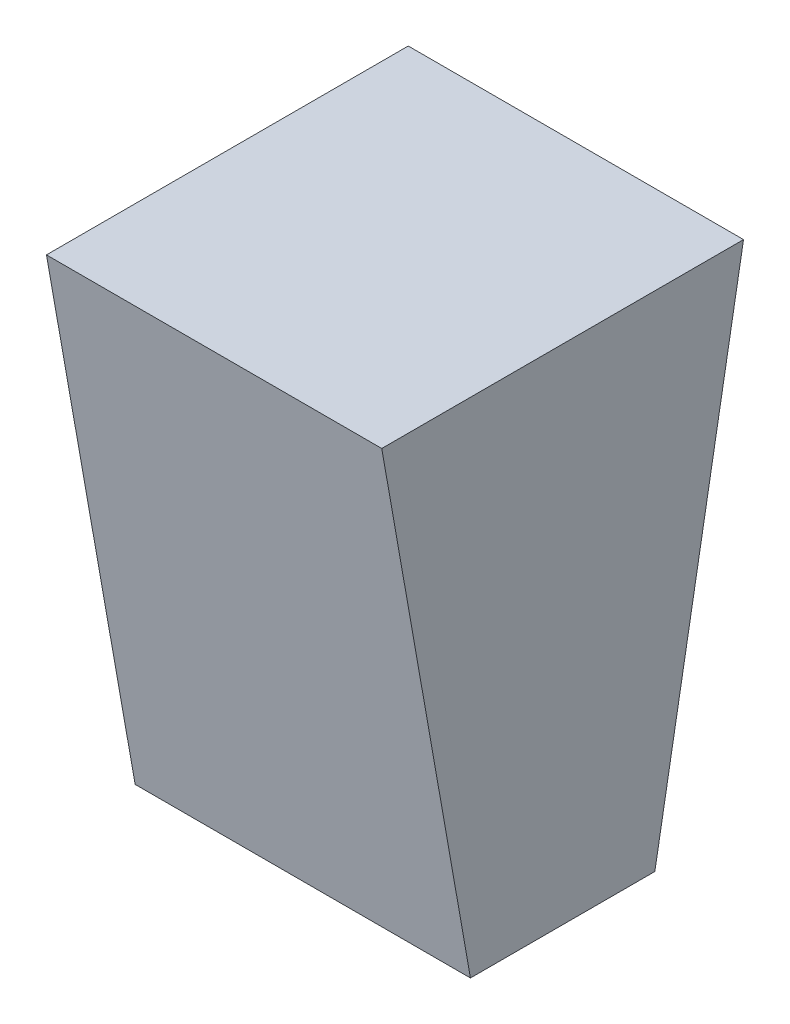
SolidWorks part; units mm, degrees
ref_plane "Alzado" through (0, 0, 0) normal (0, 0, 1) x (1, 0, 0)
ref_plane "Planta" through (0, 0, 0) normal (0, 1, 0) x (1, 0, 0)
ref_plane "Vista lateral" through (0, 0, 0) normal (1, 0, 0) x (0, 0, -1)
sketch "Croquis1" plane through (0, 0, 0) normal (1, 0, 0) x (0, 0, -1)
  line L0 (0, 0) -> (110, 0)
  line L4 (110, 0) -> (162.8981, 300)
  line L5 (0, 0) -> (-52.8981, 300)
  line L6 (-52.8981, 300) -> (162.8981, 300)
  dimension "D1" = 110
  dimension "D2" = 300
  dimension "D3" = 80
  dimension "D4" = 80
  dimension "D5" = 300
extrude "Saliente-Extruir1" add sketch "Croquis1" along normal blind 200
